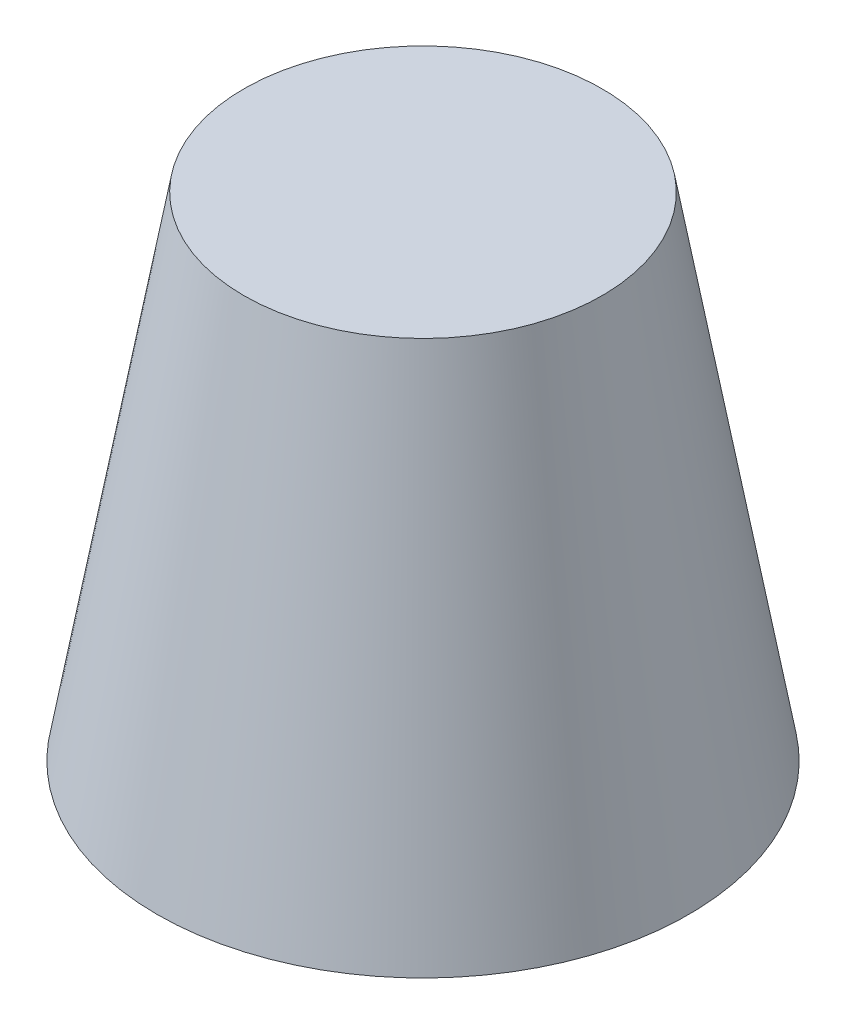
SolidWorks part; units mm, degrees
material "ABS"
ref_plane "Front Plane" through (0, 0, 0) normal (0, 0, 1) x (1, 0, 0)
ref_plane "Top Plane" through (0, 0, 0) normal (0, 1, 0) x (1, 0, 0)
ref_plane "Right Plane" through (0, 0, 0) normal (1, 0, 0) x (0, 0, -1)
sketch "Sketch1" plane through (0, 0, 0) normal (0, 0, 1) x (1, 0, 0)
  line L0 (0, 0) -> (37.0417, 0)
  line L1 (0, 0) -> (37.0417, 0) construction
  line L2 (0, 0) -> (0, 68.58) construction
  line L3 (0, 68.58) -> (37.0417, 68.58) construction
  line L4 (37.0417, 0) -> (37.0417, 68.58) construction
  line L5 (37.0417, 0) -> (24.9492, 68.58)
  line L6 (24.9492, 68.58) -> (0, 68.58)
  line L7 (0, 68.58) -> (0, 0)
  dimension "D1" = 37.0417
  dimension "D2" = 68.58
  dimension "D3" = 80
revolve "Revolve1" add sketch "Sketch1" angle 360 about L7
shell "Shell1" thickness 2.54
